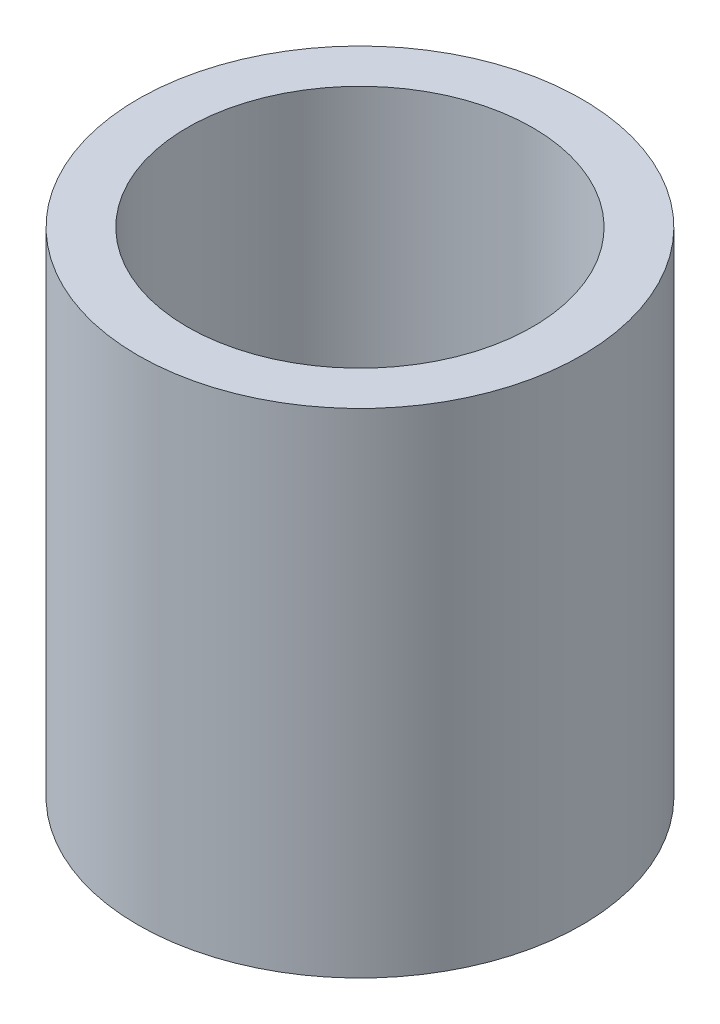
SolidWorks part; units mm, degrees
ref_plane "Front Plane" through (0, 0, 0) normal (0, 0, 1) x (1, 0, 0)
ref_plane "Top Plane" through (0, 0, 0) normal (0, 1, 0) x (1, 0, 0)
ref_plane "Right Plane" through (0, 0, 0) normal (1, 0, 0) x (0, 0, -1)
sketch "Sketch1" plane through (0, 0, 0) normal (0, 1, 0) x (1, 0, 0)
  circle A0 centre (0, 0) radius 4.5
  circle A1 centre (0, 0) radius 3.5
  dimension "D1" = 7
  dimension "D2" = 9
extrude "Boss-Extrude1" add sketch "Sketch1" along normal blind 10
